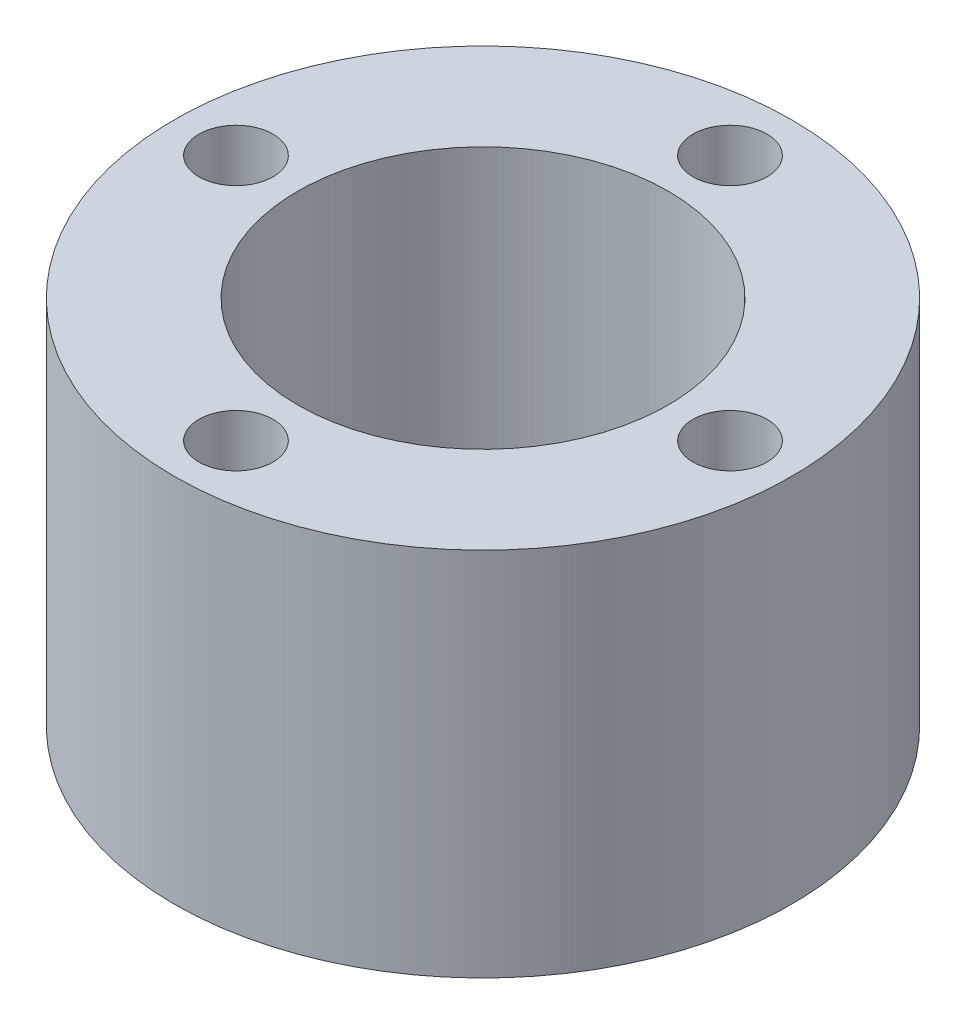
SolidWorks part; units mm, degrees
ref_plane "Front Plane" through (0, 0, 0) normal (0, 0, 1) x (1, 0, 0)
ref_plane "Top Plane" through (0, 0, 0) normal (0, 1, 0) x (1, 0, 0)
ref_plane "Right Plane" through (0, 0, 0) normal (1, 0, 0) x (0, 0, -1)
sketch "Sketch1" plane through (0, 0, 0) normal (0, 1, 0) x (1, 0, 0)
  circle A0 centre (0, 0) radius 15
  circle A1 centre (0, 0) radius 25
  dimension "D1" = 30
  dimension "D2" = 50
extrude "Boss-Extrude1" add sketch "Sketch1" along normal blind 30
sketch "Sketch2" plane through (0, 30, 0) normal (0, 1, 0) x (1, 0, 0)
  circle A0 centre (0, 0) radius 20
  circle A1 centre (0, 20) radius 3
  circle A2 centre (20, 0) radius 3
  circle A3 centre (0, -20) radius 3
  circle A4 centre (-20, 0) radius 3
  point P14 (0, 0)
  dimension "D2" = 6
  dimension "D3" = 40
  dimension "D1" = 4
extrude "Cut-Extrude1" cut sketch "Sketch2" against normal blind 30 contours A4 | A1 | A2 | A3
